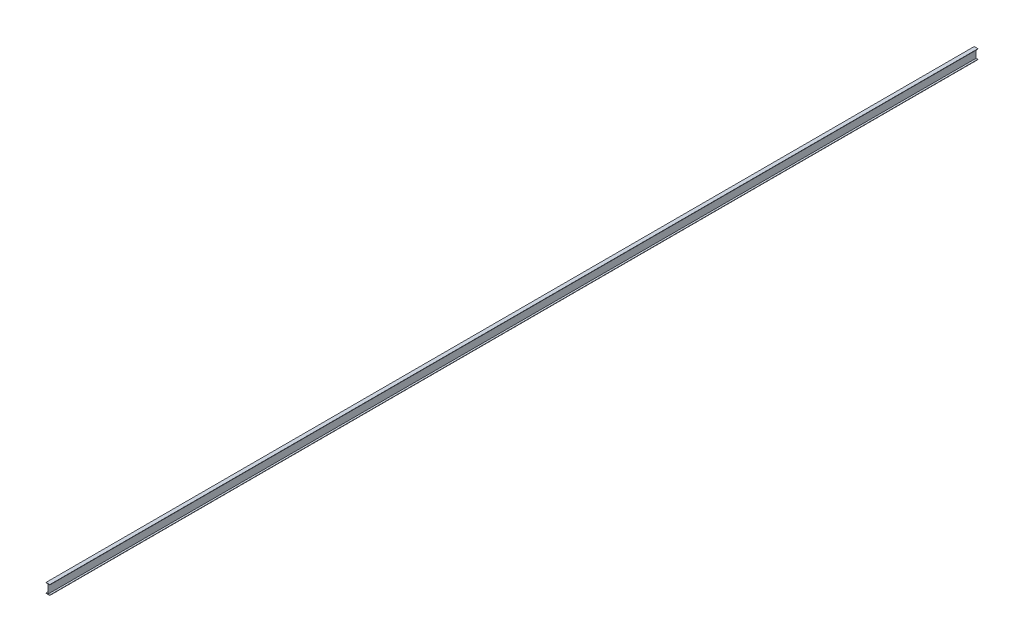
SolidWorks part; units mm, degrees
ref_plane "Front Plane" through (0, 0, 0) normal (0, 0, 1) x (1, 0, 0)
ref_plane "Top Plane" through (0, 0, 0) normal (0, 1, 0) x (1, 0, 0)
ref_plane "Right Plane" through (0, 0, 0) normal (1, 0, 0) x (0, 0, -1)
sketch "Sketch1" plane through (0, 0, 0) normal (0, 0, 1) x (1, 0, 0)
  line L0 (100, 0) -> (100, 16)
  line L1 (-100, 500) -> (-100, 484)
  line L2 (-100, 0) -> (100, 0)
  line L3 (-100, 0) -> (-100, 16)
  line L4 (-100, 500) -> (100, 500)
  line L5 (100, 484) -> (100, 500)
  line L6 (-100, 16) -> (-5.0996, 16)
  line L7 (-5.0996, 484) -> (-5.0996, 16)
  line L8 (-100, 484) -> (-5.0996, 484)
  line L9 (5.1, 484) -> (100, 484)
  line L10 (5.1, 16) -> (5.1, 484)
  line L11 (5.1, 16) -> (100, 16)
extrude "Boss-Extrude1" add sketch "Sketch1" along normal blind 49152
